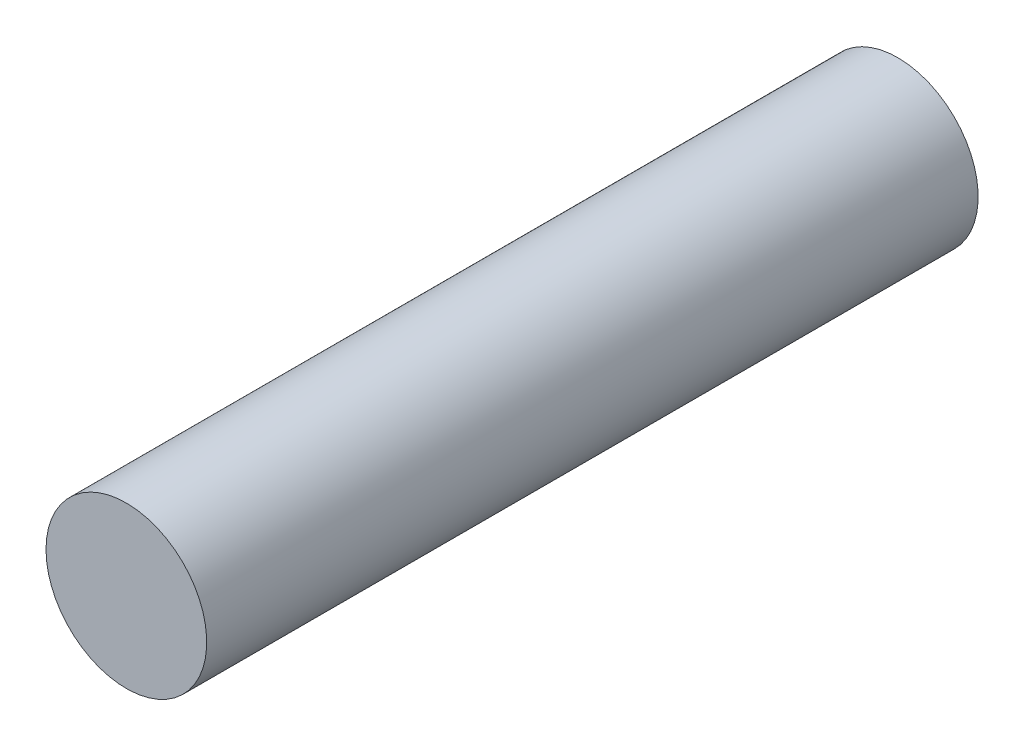
SolidWorks part; units mm, degrees
ref_plane "Front Plane" through (0, 0, 0) normal (0, 0, 1) x (1, 0, 0)
ref_plane "Top Plane" through (0, 0, 0) normal (0, 1, 0) x (1, 0, 0)
ref_plane "Right Plane" through (0, 0, 0) normal (1, 0, 0) x (0, 0, -1)
sketch "Sketch1" plane through (0, 0, 0) normal (0, 0, 1) x (1, 0, 0)
  circle A0 centre (0, 0) radius 1.5875
  dimension "D1" = 3.175
extrude "Boss-Extrude1" add sketch "Sketch1" along normal blind 15.24
